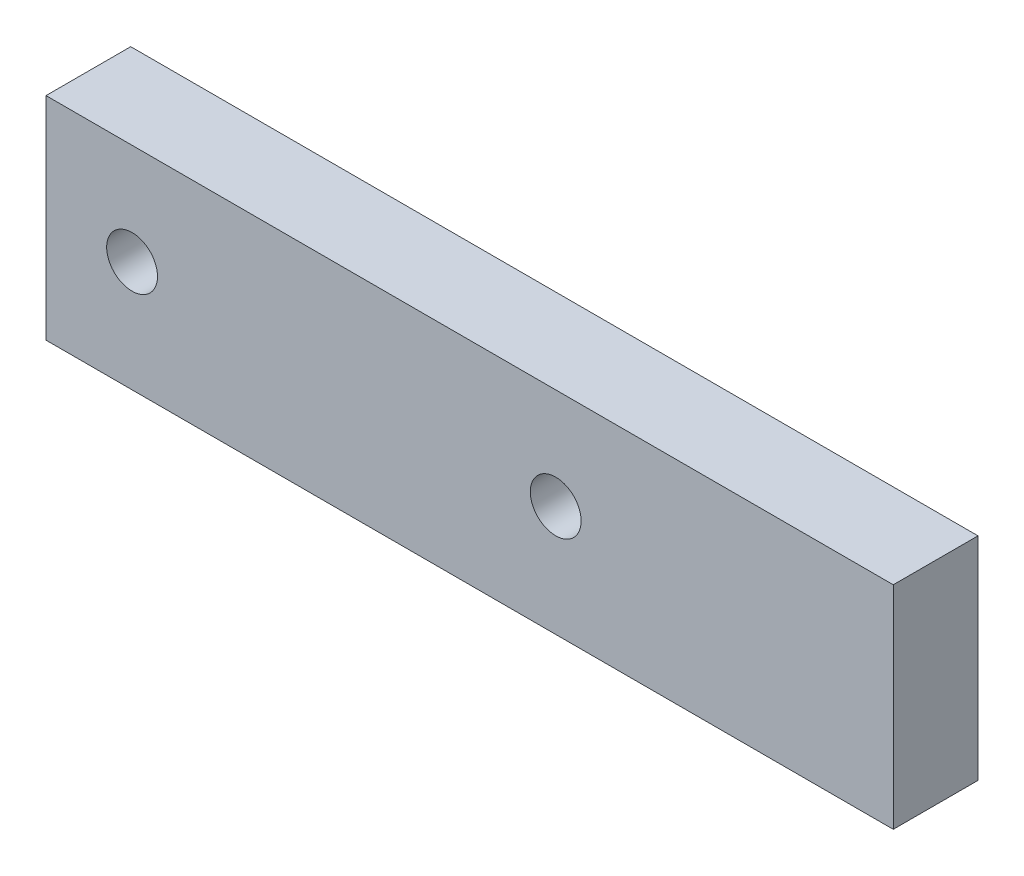
SolidWorks part; units mm, degrees
ref_plane "Front Plane" through (0, 0, 0) normal (0, 0, 1) x (1, 0, 0)
ref_plane "Top Plane" through (0, 0, 0) normal (0, 1, 0) x (1, 0, 0)
ref_plane "Right Plane" through (0, 0, 0) normal (1, 0, 0) x (0, 0, -1)
sketch "Sketch1" plane through (0, 0, 0) normal (0, 0, 1) x (1, 0, 0)
  line L1 (-37.6596, 11.9149) -> (62.3404, 11.9149)
  line L2 (-37.6596, 11.9149) -> (-37.6596, -13.0851)
  line L3 (-37.6596, -13.0851) -> (62.3404, -13.0851)
  line L4 (62.3404, 11.9149) -> (62.3404, -13.0851)
  dimension "D1" = 100
  dimension "D2" = 25
extrude "Boss-Extrude1" add sketch "Sketch1" along normal blind 10
sketch "Sketch2" plane through (0, 0, 10) normal (0, 0, 1) x (1, 0, 0)
  circle A0 centre (-27.5004, 0) radius 3
  point P2 (0, 0)
  point P3 (0, 0)
  dimension "D1" = 6
extrude "Cut-Extrude1" cut sketch "Sketch2" against normal blind 10
sketch "Sketch3" plane through (0, 0, 10) normal (0, 0, 1) x (1, 0, 0)
  circle A0 centre (22.4996, 0) radius 3
  circle A1 centre (-27.5004, 0) radius 3 construction
  point P4 (0, 0)
  dimension "D1" = 6
  dimension "D2" = 50
extrude "Cut-Extrude2" cut sketch "Sketch3" against normal blind 10
